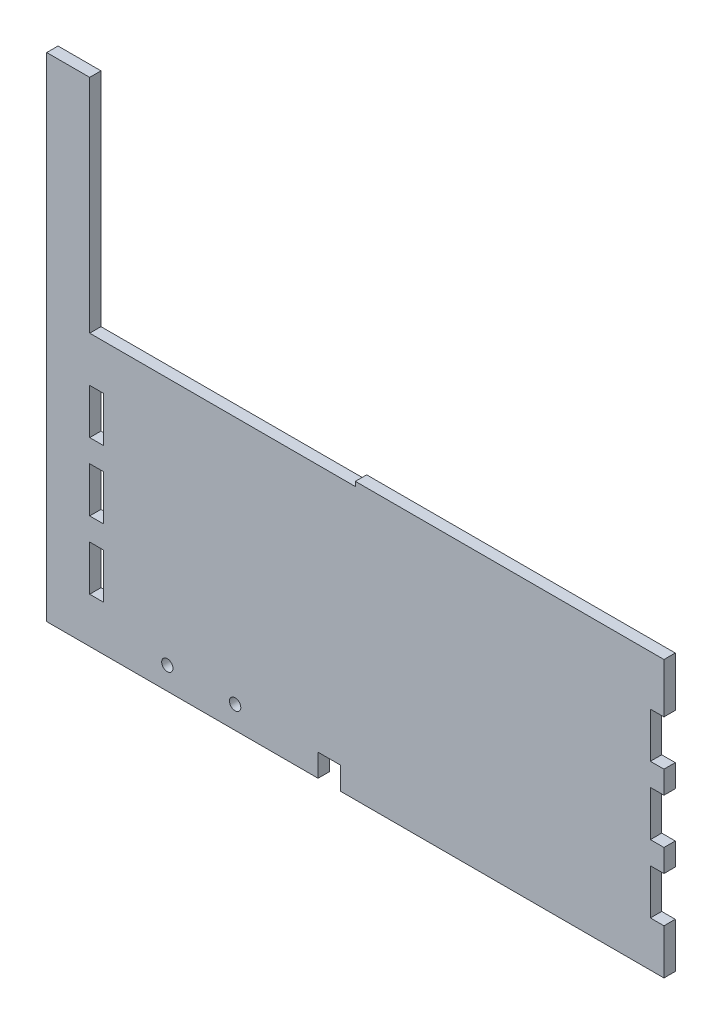
SolidWorks part; units mm, degrees
ref_plane "Front Plane" through (0, 0, 0) normal (0, 0, 1) x (1, 0, 0)
ref_plane "Top Plane" through (0, 0, 0) normal (0, 1, 0) x (1, 0, 0)
ref_plane "Right Plane" through (0, 0, 0) normal (1, 0, 0) x (0, 0, -1)
sketch "Sketch1" plane through (0, 0, 0) normal (0, 0, 1) x (1, 0, 0)
  line L1 (-136.5, -61) -> (136.5, -61)
  line L2 (-136.5, -61) -> (-136.5, 61)
  line L3 (-136.5, 61) -> (136.5, 61)
  line L4 (136.5, -61) -> (136.5, 61)
  line L5 (0, 61) -> (0, -61) construction
  line L6 (-136.5, 0) -> (136.5, 0) construction
  point P0 (0, 0)
  dimension "D1" = 273
  dimension "D2" = 122
extrude "Boss-Extrude1" add sketch "Sketch1" along normal blind 5
sketch "Sketch2" plane through (0, 0, 5) normal (0, 0, 1) x (1, 0, 0)
  line L1 (-136.5, 61) -> (-117.5, 61)
  line L2 (-136.5, 61) -> (-136.5, 157)
  line L3 (-136.5, 157) -> (-117.5, 157)
  line L4 (-117.5, 61) -> (-117.5, 157)
  dimension "D1" = 96
  dimension "D2" = 19
extrude "Boss-Extrude2" add sketch "Sketch2" against normal blind 5
sketch "Sketch3" plane through (0, 0, 5) normal (0, 0, 1) x (1, 0, 0)
  line L1 (-117.5, 61) -> (136.5, 61)
  line L2 (-117.5, 61) -> (-117.5, -61)
  line L3 (-117.5, -61) -> (136.5, -61)
  line L4 (136.5, 61) -> (136.5, -61)
  line L5 (130.5, 39) -> (142.5, 39)
  line L6 (130.5, 39) -> (130.5, 19)
  line L7 (130.5, 19) -> (142.5, 19)
  line L8 (142.5, 39) -> (142.5, 19)
  line L9 (136.5, 19) -> (136.5, 39) construction
  line L10 (130.5, 29) -> (142.5, 29) construction
  line L11 (130.5, -11) -> (142.5, -11)
  line L12 (130.5, -11) -> (130.5, 9)
  line L13 (130.5, 9) -> (142.5, 9)
  line L14 (142.5, -11) -> (142.5, 9)
  line L15 (136.5, 9) -> (136.5, -11) construction
  line L16 (130.5, -1) -> (142.5, -1) construction
  line L17 (130.5, -41) -> (142.5, -41)
  line L18 (130.5, -41) -> (130.5, -21)
  line L19 (130.5, -21) -> (142.5, -21)
  line L20 (142.5, -41) -> (142.5, -21)
  line L21 (136.5, -21) -> (136.5, -41) construction
  line L22 (130.5, -31) -> (142.5, -31) construction
  line L23 (-123.5, 39) -> (-111.5, 39)
  line L24 (-123.5, 39) -> (-123.5, 19)
  line L25 (-123.5, 19) -> (-111.5, 19)
  line L26 (-111.5, 39) -> (-111.5, 19)
  line L27 (-117.5, 19) -> (-117.5, 39) construction
  line L28 (-123.5, 29) -> (-111.5, 29) construction
  line L29 (-123.5, -11) -> (-111.5, -11)
  line L30 (-123.5, -11) -> (-123.5, 9)
  line L31 (-123.5, 9) -> (-111.5, 9)
  line L32 (-111.5, -11) -> (-111.5, 9)
  line L33 (-117.5, 9) -> (-117.5, -11) construction
  line L34 (-123.5, -1) -> (-111.5, -1) construction
  line L35 (-123.5, -41) -> (-111.5, -41)
  line L36 (-123.5, -41) -> (-123.5, -21)
  line L37 (-123.5, -21) -> (-111.5, -21)
  line L38 (-111.5, -41) -> (-111.5, -21)
  line L39 (-117.5, -21) -> (-117.5, -41) construction
  line L40 (-123.5, -31) -> (-111.5, -31) construction
  point P6 (136.5, 29)
  point P10 (136.5, -1)
  point P14 (136.5, -31)
  point P18 (-117.5, 29)
  point P22 (-117.5, -1)
  point P26 (-117.5, -31)
  dimension "D1" = 30
  dimension "D2" = 30
  dimension "D3" = 30
  dimension "D4" = 12
  dimension "D5" = 12
  dimension "D6" = 12
  dimension "D7" = 20
  dimension "D8" = 20
  dimension "D9" = 20
  dimension "D10" = 12
  dimension "D11" = 12
  dimension "D12" = 12
  dimension "D13" = 20
  dimension "D14" = 20
  dimension "D15" = 20
  dimension "D16" = 30
  dimension "D17" = 30
  dimension "D18" = 30
extrude "Cut-Extrude1" cut sketch "Sketch3" against normal blind 6 contours L26 L23 L2 L25 | L29 L32 L31 L2 | L35 L38 L37 L2 | L6 L7 L4 L5 | L13 L12 L11 L4 | L19 L18 L17 L4
sketch "Sketch6" plane through (0, 0, 5) normal (0, 0, 1) x (1, 0, 0)
  line L1 (-117.5, 61) -> (136.5, 61)
  line L2 (-117.5, 61) -> (-117.5, -61)
  line L3 (-117.5, -61) -> (136.5, -61)
  line L4 (136.5, 61) -> (136.5, -61)
  line L5 (-117.5, 61) -> (136.5, 61)
  line L6 (-117.5, 61) -> (-117.5, 59)
  line L7 (-117.5, 59) -> (136.5, 59)
  line L8 (136.5, 61) -> (136.5, 59)
  line L9 (-117.5, 61) -> (0, 61)
  line L10 (-117.5, 61) -> (-117.5, 59)
  line L11 (-117.5, 59) -> (0, 59)
  line L12 (0, 61) -> (0, 59)
  dimension "D1" = 2
extrude "Cut-Extrude3" cut sketch "Sketch6" against normal blind 6 contours L12 L5 L2 L7
sketch "Sketch7" plane through (0, 0, 5) normal (0, 0, 1) x (1, 0, 0)
  line L0 (-83.1707, -61) -> (-83.1707, -51)
  line L1 (-136.5, -61) -> (136.5, -61) construction
  line L2 (-83.1707, -51) -> (-53.1707, -51)
  line L3 (-53.1707, -51) -> (-53.1707, -61)
  line L4 (-53.1707, -61) -> (-83.1707, -61)
  circle A0 centre (-83.1707, -51) radius 2.5
  circle A1 centre (-53.1707, -51) radius 2.5
  dimension "D3" = 5
  dimension "D4" = 5
  dimension "D1" = 10
  dimension "D2" = 30
extrude "Cut-Extrude4" cut sketch "Sketch7" against normal blind 10 contours L2 A0 L0 | L0 A0 L2 | L3 A1 L2 | L2 A1 L3
sketch "Sketch8" plane through (0, 0, 5) normal (0, 0, 1) x (1, 0, 0)
  line L0 (-136.5, -61) -> (136.5, -61) construction
  line L1 (-16.5, -61) -> (-6.5, -61)
  line L2 (-16.5, -61) -> (-16.5, -51)
  line L3 (-16.5, -51) -> (-6.5, -51)
  line L4 (-6.5, -61) -> (-6.5, -51)
  dimension "D1" = 10
  dimension "D2" = 10
  dimension "D3" = 120
extrude "Cut-Extrude5" cut sketch "Sketch8" against normal blind 10
